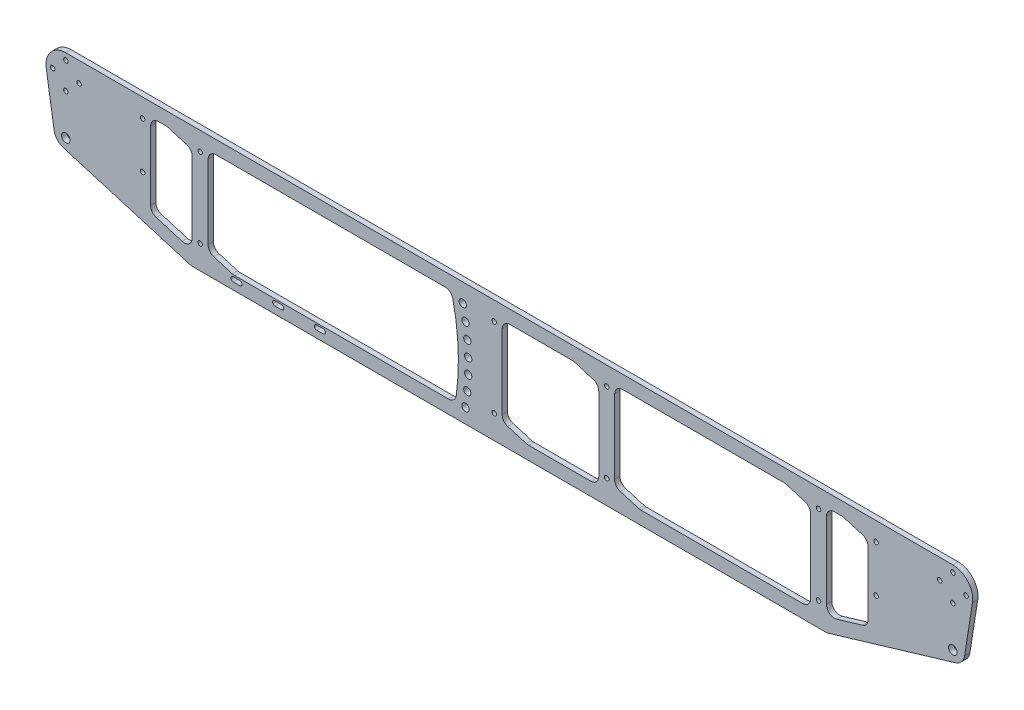
SolidWorks part; units mm, degrees
material "Сплав 2024"
ref_plane "Спереди" through (0, 0, 0) normal (0, 0, 1) x (1, 0, 0)
ref_plane "Сверху" through (0, 0, 0) normal (0, 1, 0) x (1, 0, 0)
ref_plane "Справа" through (0, 0, 0) normal (1, 0, 0) x (0, 0, -1)
sketch "Эскиз1" plane through (0, 0, 0) normal (0, 0, 1) x (1, 0, 0)
  line L0 (-349.8183, 28.6724) -> (-342.9109, -15.3036)
  line L1 (-350, 46) -> (350, 46) construction
  line L2 (-350, 46) -> (-350, -46) construction
  line L3 (-350, -46) -> (350, -46) construction
  line L4 (350, 46) -> (350, -46) construction
  line L5 (-350, 46) -> (350, -46) construction
  line L6 (-350, -46) -> (350, 46) construction
  line L7 (-342.9109, -15.3036) -> (-240, -46)
  line L9 (0, 62.4154) -> (0, -74.3401) construction
  line L10 (-240, -46) -> (240, -46)
  line L12 (-335, 46) -> (335, 46)
  line L15 (342.9109, -15.3036) -> (240, -46)
  line L16 (349.8183, 28.6724) -> (342.9109, -15.3036)
  arc A0 (-335, 46) -> (-349.8183, 28.6724) centre (-335, 31) ccw
  arc A1 (335, 46) -> (349.8183, 28.6724) centre (335, 31) cw
  circle A2 centre (-335, -9.6353) radius 3.25
  circle A3 centre (335, -9.6353) radius 3.25
  point P0 (0, 0)
  point P20 (0, 46)
  point P21 (0, -46)
  dimension "D3" = 30
  dimension "D4" = 6.5
  dimension "D1" = 700
  dimension "D2" = 92
  dimension "D5" = 480
extrude "Бобышка-Вытянуть1" add sketch "Эскиз1" along normal blind 4
sketch "Эскиз2" plane through (0, 0, 4) normal (0, 0, 1) x (1, 0, 0)
  line L0 (0, 49.4785) -> (0, -75.5602) construction
  line L1 (-350, 31) -> (-320, 31) construction
  line L2 (-335, 46) -> (-335, 16) construction
  line L3 (335, 46) -> (335, 16) construction
  line L4 (350, 31) -> (320, 31) construction
  circle A0 centre (-335, 31) radius 15 construction
  arc A1 (-335, 46) -> (-349.8183, 28.6724) centre (-335, 31) ccw construction
  circle A2 centre (-335, 31) radius 10 construction
  circle A4 centre (335, 31) radius 10 construction
  circle A5 centre (335, 31) radius 15 construction
  dimension "D2" = 20
hole_wizard "Отверстие с зазором M32" positions "Эскиз4" profile "Эскиз3" hole size "M3" standard "Ansi Metric" end condition through all
sketch "Эскиз4" plane through (0, 0, 4) normal (0, 0, 1) x (1, 0, 0)
  line L0 (-335, 46) -> (-335, 16) construction
  line L1 (-350, 31) -> (-320, 31) construction
  line L2 (350, 31) -> (320, 31) construction
  line L3 (335, 46) -> (335, 16) construction
  circle A0 centre (-335, 31) radius 10 construction
  circle A1 centre (335, 31) radius 10 construction
  point P0 (-335, 41)
  point P6 (-345, 31)
  point P10 (-335, 21)
  point P12 (-325, 31)
  point P34 (325, 31)
  point P40 (335, 41)
  point P44 (345, 31)
  point P46 (335, 21)
sketch "Эскиз3" plane through (-335, 41, 4) normal (1, 0, 0) x (0, -1, 0)
  line L0 (0, 0) -> (0, 4)
  line L1 (0, 4) -> (1.7, 4)
  line L2 (1.7, 4) -> (1.7, 0)
  line L5 (1.7, 0) -> (0, 0)
  line L11 (0, -6.35) -> (0, 107.95) construction
  dimension "Диаметр сквозного отверстия" = 3.4
  dimension "Глубина сквозного отверстия" = 4
sketch "Эскиз7" plane through (0, 0, 0) normal (0, 0, -1) x (-1, 0, 0)
  line L1 (240, -46) -> (-240, -46) construction
  arc A1 (349.8183, 28.6724) -> (335, 46) centre (335, 31) ccw construction
  point P4 (215, -7)
  dimension "D1" = 120
  dimension "D2" = 39
hole_wizard "Отверстие с зазором M52" positions "Эскиз9" profile "Эскиз8" hole size "M5" standard "Ansi Metric" end condition through all
sketch "Эскиз9" plane through (0, 0, 0) normal (0, 0, -1) x (-1, 0, 0)
  point P3 (215, -7)
sketch "Эскиз8" plane through (-215, -7, 0) normal (1, 0, 0) x (0, 1, 0)
  line L0 (0, 0) -> (0, 4)
  line L1 (0, 4) -> (2.75, 4)
  line L2 (2.75, 4) -> (2.75, 0)
  line L5 (2.75, 0) -> (0, 0)
  line L11 (0, -6.35) -> (0, 107.95) construction
  dimension "Диаметр сквозного отверстия" = 5.5
  dimension "Глубина сквозного отверстия" = 4
sketch "Эскиз10" plane through (0, 0, 4) normal (0, 0, 1) x (1, 0, 0)
  line L0 (-299.3246, 36) -> (-255.3246, 36)
  line L1 (335, 46) -> (-335, 46) construction
  line L2 (-299.3246, 36) -> (-299.3246, -17.8692)
  line L3 (-299.3246, -17.8692) -> (-244.0344, -34.3612)
  line L4 (0, 46) -> (0, -46) construction
  line L5 (-342.9109, -15.3036) -> (-240, -46) construction
  line L6 (-225.2731, 36) -> (-56.1536, 36)
  line L7 (-238.5404, -36) -> (-53.9475, -36)
  line L8 (-240, -46) -> (240, -46) construction
  line L9 (-255.3246, 36) -> (-240.437, -30.0467)
  line L11 (-300.3246, -20.6159) -> (-300.3246, 44.3841) construction
  line L12 (271.818, 36) -> (271.818, -17.9187)
  line L13 (271.818, -17.9187) -> (224.0901, -33.1261)
  line L14 (271.818, 36) -> (224.0901, 36)
  line L15 (224.0901, 36) -> (224.0901, -33.1261)
  line L17 (212.0901, 36) -> (121.9708, 36)
  line L19 (-272.9676, -25.731) -> (-174.3183, -55.1562) construction
  line L20 (0.7585, 21.0494) -> (0.7585, -36)
  line L21 (0.7585, -36) -> (18.1269, -36)
  line L22 (212.0901, -21.0494) -> (212.0901, 36)
  line L23 (65.0489, 36) -> (65.0489, -21.0494)
  line L24 (75.0489, 21.0494) -> (75.0489, -36)
  line L25 (47.6805, 36) -> (0.7585, 21.0494)
  line L26 (212.0901, -21.0494) -> (165.1682, -36)
  line L27 (-140.8515, 55.5349) -> (-140.8515, -67.5658) construction
  line L28 (75.0489, -36) -> (165.1682, -36)
  line L29 (121.9708, 36) -> (75.0489, 21.0494)
  line L30 (65.0489, -21.0494) -> (18.1269, -36)
  line L31 (-238.5404, -36) -> (-218.7965, -12.3203)
  line L32 (-225.2731, 36) -> (-216.5143, -2.8572)
  line L33 (-164.0688, -36) -> (-228.2742, -36) construction
  line L34 (65.0489, 36) -> (47.6805, 36)
  line L35 (-240.437, -30.0467) -> (-244.0344, -34.3612)
  line L36 (272.818, 44.3841) -> (272.818, -20.6159) construction
  line L37 (223.0901, 43) -> (223.0901, -42) construction
  line L38 (213.0901, 43) -> (213.0901, -42) construction
  arc A0 (-53.9475, -36) -> (-56.1536, 36) centre (-227.2451, -5.276) ccw
  arc A1 (-216.5143, -2.8572) -> (-218.7965, -12.3203) centre (-227.2451, -5.276) cw
  dimension "D4" = 1
  dimension "D5" = 1
  dimension "D2" = 1
  dimension "D10" = 11
  dimension "D12" = 176
  dimension "D1" = 10
  dimension "D3" = 10
  dimension "D6" = 10
  dimension "D7" = 10
  dimension "D8" = 1
  dimension "D9" = 44
  dimension "D11" = 57.0494
extrude "Вырез-Вытянуть3" [suppressed] cut sketch "Эскиз10" against normal through all
fillet "Скругление2" [suppressed] radius 10
fillet "Скругление3" [suppressed] radius 10
sketch "Эскиз14" plane through (0, 0, 4) normal (0, 0, 1) x (1, 0, 0)
  line L0 (0, 59.2479) -> (0, -65.4566) construction
fillet "Скругление4" [suppressed] radius 8
sketch "Эскиз15" plane through (0, 0, 0) normal (0, 0, 1) x (1, 0, 0)
  line L0 (-350, 110.1025) -> (-350, -46) construction
  line L1 (-350, -46) -> (-196.6137, -46) construction
  line L2 (-240, -46) -> (240, -46) construction
  line L3 (350, 94.0601) -> (350, -69.6023) construction
  arc A0 (-335, 46) -> (-349.8183, 28.6724) centre (-335, 31) ccw construction
  arc A1 (349.8183, 28.6724) -> (335, 46) centre (335, 31) ccw construction
sketch "Эскиз17" plane through (0, 0, 0) normal (0, 0, -1) x (-1, 0, 0)
  line L0 (-277, 66.2572) -> (-277, -56.845) construction
  line L1 (-335, 46) -> (335, 46) construction
  line L2 (234.2682, -7) -> (-30.3456, -7) construction
  line L3 (0, 46) -> (0, 69.3185) construction
  line L4 (215, -7) -> (-69.7478, 19.1646) construction
  line L5 (240, -46) -> (-240, -46) construction
  line L6 (215, -7) -> (-66.6882, 1.6064) construction
  line L7 (215, -7) -> (-14.665, -14.0169) construction
  line L8 (215, -7) -> (-40.5191, 32.3282) construction
  line L9 (215, -7) -> (-47.5026, 49.9949) construction
  line L10 (215, -7) -> (-21.1437, -28.6986) construction
  line L11 (215, -7) -> (-22.6665, -43.5804) construction
  arc A0 (-335, 46) -> (-349.8183, 28.6724) centre (-335, 31) ccw construction
  arc A1 (36.6847, -52.3836) -> (42.8196, 57.8837) centre (215, -7) cw construction
  point P2 (-277, 31)
  point P3 (-277, -4)
  point P9 (277, 31)
  point P10 (277, -4)
  point P20 (31.7713, 9.83)
  dimension "D3" = 58
  dimension "D4" = 184
  dimension "D1" = 15
  dimension "D2" = 35
  dimension "D5" = 55.83
  dimension "D6" = 1.75
  dimension "D7" = 3.5
  dimension "D8" = 3.5
  dimension "D9" = 3.5
  dimension "D10" = 1.75
  dimension "D11" = 3.5
  dimension "D12" = 3.5
hole_wizard "Отверстие с зазором M33" [suppressed] positions "Эскиз19" profile "Эскиз18" hole size "M3" standard "Ansi Metric"
sketch "Эскиз19" [suppressed] plane through (0, 0, 0) normal (0, 0, -1) x (-1, 0, 0)
  point P0 (-277, 31)
  point P5 (-277, -4)
  point P8 (277, -4)
  point P11 (277, 31)
sketch "Эскиз18" plane through (277, 31, 0) normal (1, 0, 0) x (0, 1, 0)
  line L0 (0, 0) -> (0, 4)
  line L1 (0, 4) -> (1.7, 4)
  line L2 (1.7, 4) -> (1.7, 0)
  line L5 (1.7, 0) -> (0, 0)
  line L11 (0, -6.35) -> (0, 107.95) construction
  dimension "Диаметр сквозного отверстия" = 3.4
  dimension "Глубина сквозного отверстия" = 4
hole_wizard "Отверстие с зазором M53" positions "Эскиз21" profile "Эскиз20" hole size "M5" standard "Ansi Metric" end condition through all
sketch "Эскиз21" plane through (0, 0, 0) normal (0, 0, -1) x (-1, 0, 0)
  line L0 (215, -7) -> (-47.5026, 49.9949) construction
  line L1 (215, -7) -> (-40.5191, 32.3282) construction
  line L2 (215, -7) -> (-66.6882, 1.6064) construction
  line L3 (215, -7) -> (-14.665, -14.0169) construction
  line L4 (215, -7) -> (-21.1437, -28.6986) construction
  line L5 (215, -7) -> (-22.6665, -43.5804) construction
  arc A0 (42.8196, 57.8837) -> (36.6847, -52.3836) centre (215, -7) ccw construction
  point P0 (31.7713, 9.83)
  point P3 (35.1895, 32.0407)
  point P10 (33.1415, 20.9907)
  point P14 (31.0858, -1.3809)
  point P18 (31.0858, -12.6191)
  point P22 (31.7719, -23.8363)
  point P26 (33.1415, -34.9907)
sketch "Эскиз20" plane through (-31.7713, 9.83, 0) normal (1, 0, 0) x (0, 1, 0)
  line L0 (0, 0) -> (0, 4)
  line L1 (0, 4) -> (2.75, 4)
  line L2 (2.75, 4) -> (2.75, 0)
  line L5 (2.75, 0) -> (0, 0)
  line L11 (0, -6.35) -> (0, 107.95) construction
  dimension "Диаметр сквозного отверстия" = 5.5
  dimension "Глубина сквозного отверстия" = 4
fillet "Скругление5" radius 10 4 edges at (342.9109, -15.3036, 2) (240, -46, 2) (-342.9109, -15.3036, 2) (-240, -46, 2)
sketch "Эскиз22" plane through (0, 0, 0) normal (0, 0, -1) x (-1, 0, 0)
  line L0 (-227.5404, -36) -> (-98.7059, -36)
  line L1 (-79.5404, -30.2833) -> (-79.5404, 36)
  line L2 (-79.5404, 36) -> (-208.3748, 36)
  line L3 (-227.5404, 30.2833) -> (-227.5404, -36)
  line L4 (-241.3987, -45.5828) -> (-336.8687, -17.1059) construction
  line L5 (227.54, -30.2833) -> (208.3744, -36)
  line L6 (-271, 30.2833) -> (-251.8344, 36)
  line L7 (238.5404, -46) -> (-238.5404, -46) construction
  line L8 (-335, 46) -> (335, 46) construction
  line L9 (-67.5404, -36) -> (-13.7059, -36)
  line L10 (5.4596, -30.2833) -> (5.4596, 36)
  line L11 (5.4596, 36) -> (-48.3748, 36)
  line L12 (-67.5404, 30.2833) -> (-67.5404, -36)
  line L13 (-227.5404, 30.2833) -> (-208.3748, 36)
  line L14 (-79.5404, -30.2833) -> (-98.7059, -36)
  line L15 (40.8987, -36) -> (208.3744, -36)
  line L16 (43.8181, 36) -> (227.54, 36)
  line L17 (227.54, 36) -> (227.54, -30.2833)
  line L19 (-67.5404, 30.2833) -> (-48.3748, 36)
  line L20 (-13.7059, -36) -> (5.4596, -30.2833)
  line L21 (239.54, 30.2833) -> (258.7056, 36)
  line L23 (-272, 42) -> (-272, -23) construction
  line L24 (-239.5404, 36) -> (-251.8344, 36)
  line L25 (-271, 30.2833) -> (-271, -26.3179)
  line L26 (-228.5404, 42) -> (-228.5404, -43) construction
  line L27 (-271, -26.3179) -> (-239.5404, -35.7017)
  line L28 (-239.5404, -35.7017) -> (-239.5404, 36)
  line L29 (-68.5404, 42) -> (-68.5404, -43) construction
  line L30 (258.7056, 36) -> (271, 36)
  line L31 (271, 36) -> (271, -26.3179)
  line L32 (271, -26.3179) -> (239.54, -35.7018)
  line L33 (239.54, -35.7018) -> (239.54, 30.2833)
  line L34 (336.8687, -17.1059) -> (241.3987, -45.5828) construction
  line L35 (6.4596, 42) -> (6.4596, -43) construction
  line L37 (272, -23) -> (272, 42) construction
  arc A0 (40.8987, -36) -> (43.8181, 36) centre (215, -7) cw
  dimension "D3" = 176.5
  dimension "D4" = 12
  dimension "D1" = 10
  dimension "D2" = 10
  dimension "D6" = 10
  dimension "D7" = 12
  dimension "D8" = 12
  dimension "D9" = 10
  dimension "D10" = 1
  dimension "D11" = 1
  dimension "D12" = 1
  dimension "D13" = 1
  dimension "D14" = 1
  dimension "D15" = 20
  dimension "D16" = 31.46
extrude "Вырез-Вытянуть4" cut sketch "Эскиз22" against normal through all
fillet "Скругление7" radius 6 27 edges at (-239.54, -35.7018, 2) (-271, -26.3179, 2) (-271, 36, 2) (-227.54, 36, 2) (-258.7056, 36, 2) (-239.54, 30.2833, 2) (-43.8181, 36, 2) (-40.8987, -36, 2) (67.5404, -36, 2) (-5.4596, -30.2833, 2) (13.7059, -36, 2) (-5.4596, 36, 2) (48.3748, 36, 2) (67.5404, 30.2833, 2) (227.5404, 30.2833, 2) (208.3748, 36, 2) (79.5404, 36, 2) (79.5404, -30.2833, 2) (98.7059, -36, 2) (227.5404, -36, 2) (239.5404, -35.7017, 2) (271, -26.3179, 2) (271, 30.2833, 2) (251.8344, 36, 2) (239.5404, 36, 2) (-208.3744, -36, 2) (-227.54, -30.2833, 2)
hole_wizard "Отверстие с зазором M34" positions "Эскиз24" profile "Эскиз23" hole size "M3" standard "Ansi Metric" end condition through all
sketch "Эскиз24" plane through (0, 0, 0) normal (0, 0, -1) x (-1, 0, 0)
  point P0 (-233.5404, 32)
  point P3 (-233.5404, -28)
  point P6 (-73.5404, -28)
  point P9 (-73.5404, 32)
  point P12 (11.4596, 32)
  point P15 (11.4596, -28)
  point P19 (277, 32)
  point P22 (277, -3)
  point P25 (-277, 32)
  point P28 (-277, -3)
  point P31 (233.54, -28)
  point P34 (233.54, 32)
sketch "Эскиз23" plane through (233.5404, 32, 0) normal (1, 0, 0) x (0, 1, 0)
  line L0 (0, 0) -> (0, 4)
  line L1 (0, 4) -> (1.7, 4)
  line L2 (1.7, 4) -> (1.7, 0)
  line L5 (1.7, 0) -> (0, 0)
  line L11 (0, -6.35) -> (0, 107.95) construction
  dimension "Диаметр сквозного отверстия" = 3.4
  dimension "Глубина сквозного отверстия" = 4
sketch "Эскиз25" plane through (0, 0, 4) normal (0, 0, 1) x (1, 0, 0)
  line L0 (-206.1415, -27.8745) -> (-206.1415, -52.0788) construction
  line L1 (-174.6415, -27.8745) -> (-174.6415, -52.0788) construction
  line L2 (-143.1415, -27.8745) -> (-143.1415, -52.0788) construction
  line L3 (-203.929, -39) -> (-45.24, -39) construction
  line L5 (-208.6415, -39) -> (-203.6415, -39) construction
  line L6 (-208.6415, -37.3) -> (-203.6415, -37.3)
  line L7 (-208.6415, -40.7) -> (-203.6415, -40.7)
  line L8 (-177.1415, -39) -> (-172.1415, -39) construction
  line L9 (-177.1415, -37.3) -> (-172.1415, -37.3)
  line L10 (-177.1415, -40.7) -> (-172.1415, -40.7)
  line L11 (-140.6415, -39) -> (-145.6415, -39) construction
  line L12 (-140.6415, -40.7) -> (-145.6415, -40.7)
  line L13 (-140.6415, -37.3) -> (-145.6415, -37.3)
  line L14 (-46.0584, -36) -> (-207.4987, -36) construction
  arc A0 (-208.6415, -37.3) -> (-208.6415, -40.7) centre (-208.6415, -39) ccw
  arc A1 (-203.6415, -40.7) -> (-203.6415, -37.3) centre (-203.6415, -39) ccw
  arc A2 (-177.1415, -37.3) -> (-177.1415, -40.7) centre (-177.1415, -39) ccw
  arc A3 (-172.1415, -40.7) -> (-172.1415, -37.3) centre (-172.1415, -39) ccw
  arc A4 (-140.6415, -40.7) -> (-140.6415, -37.3) centre (-140.6415, -39) ccw
  arc A5 (-145.6415, -37.3) -> (-145.6415, -40.7) centre (-145.6415, -39) ccw
  circle A6 centre (-33.1415, -34.9907) radius 2.75 construction
  point P12 (-206.1415, -39)
  point P19 (-174.6415, -39)
  point P25 (-143.1415, -39)
  dimension "D5" = 1.7
  dimension "D8" = 1.7
  dimension "D9" = 1.7
  dimension "D1" = 31.5
  dimension "D2" = 31.5
  dimension "D3" = 3
  dimension "D4" = 5
  dimension "D6" = 5
  dimension "D7" = 5
  dimension "D10" = 110
extrude "Вырез-Вытянуть5" cut sketch "Эскиз25" against normal through all
